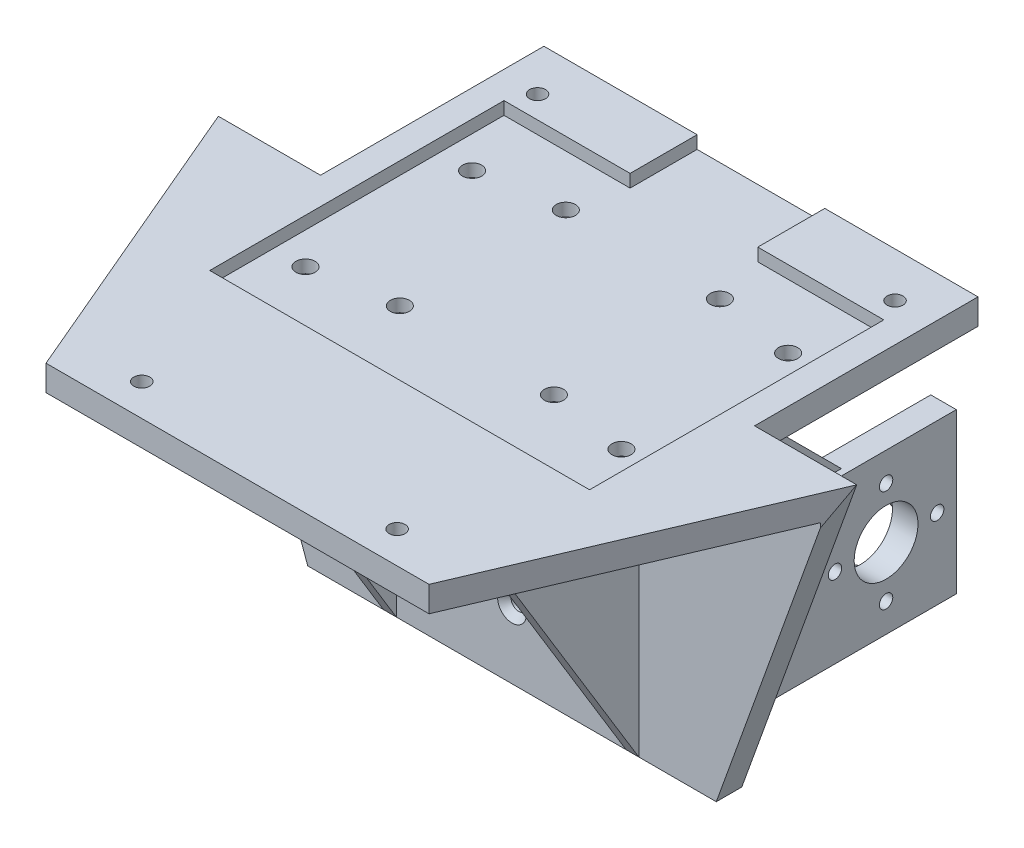
SolidWorks part; units mm, degrees
ref_plane "前视基准面" through (0, 0, 0) normal (0, 0, 1) x (1, 0, 0)
ref_plane "上视基准面" through (0, 0, 0) normal (0, 1, 0) x (1, 0, 0)
ref_plane "右视基准面" through (0, 0, 0) normal (1, 0, 0) x (0, 0, -1)
sketch "草图1" plane through (0, 0, 0) normal (1, 0, 0) x (0, 0, -1)
  line L1 (0, 0) -> (-47, 0)
  line L2 (0, 0) -> (0, 50)
  line L3 (0, 50) -> (-47, 50)
  line L4 (-47, 0) -> (-47, 50)
  point P4 (0, 0)
extrude "凸台-拉伸1" add sketch "草图1" against normal blind 100
sketch "草图2" plane through (0, 0, 0) normal (1, 0, 0) x (0, 0, -1)
  line L1 (-47, 0) -> (-4, 0)
  line L2 (-47, 0) -> (-47, 46)
  line L3 (-47, 46) -> (-4, 46)
  line L4 (-4, 0) -> (-4, 46)
  point P4 (0, 0)
  point P5 (0, 0)
extrude "切除-拉伸1" cut sketch "草图2" against normal through all
sketch "草图6" plane through (0, 0, 4) normal (0, 0, 1) x (1, 0, 0)
  circle A0 centre (-58, 26.5) radius 1
  circle A1 centre (-58, 18.5) radius 1
  circle A2 centre (-58, 10.5) radius 1
  circle A3 centre (-50, 26.5) radius 1
  circle A4 centre (-42, 26.5) radius 1
  circle A5 centre (-50, 18.5) radius 1
  circle A6 centre (-42, 18.5) radius 1
  circle A7 centre (-50, 10.5) radius 1
  circle A8 centre (-42, 10.5) radius 1
hole_wizard "打孔尺寸(%根据十字)槽沉头木螺钉的类型1" positions "草图29" profile "草图30" countersink size "M2" standard "GB" end condition through all
sketch "草图29" plane through (0, 0, 4) normal (0, 0, 1) x (1, 0, 0)
  point P0 (-58, 26.5)
  point P3 (-50, 26.5)
  point P6 (-58, 18.5)
  point P9 (-50, 18.5)
  point P12 (-58, 10.5)
  point P15 (-50, 10.5)
  point P18 (-42, 10.5)
  point P21 (-42, 18.5)
  point P24 (-42, 26.5)
sketch "草图30" plane through (-58, 26.5, 4) normal (1, 0, 0) x (0, -1, 0)
  line L0 (0, 0) -> (0, 4)
  line L1 (0, 4) -> (1.2, 4)
  line L2 (1.2, 4) -> (1.2, 1.05)
  line L3 (1.2, 1.05) -> (2.25, 0)
  line L5 (2.25, 0) -> (0, 0)
  line L6 (-1.2, 1.05) -> (-2.25, 0) construction
  line L11 (0, -6.35) -> (0, 107.95) construction
  dimension "通孔孔直径" = 2.4
  dimension "通孔孔深度" = 4
  dimension "近端锥形沉头孔直径" = 4.5
  dimension "近端锥形沉头孔角度" = 90
sketch "草图31" plane through (0, 0, 0) normal (0, 0, -1) x (-1, 0, 0)
  line L0 (21.4, 6) -> (25.4, 6)
  line L6 (25.4, 6) -> (25.4, 31)
  line L7 (25.4, 31) -> (21.4, 31)
  line L8 (21.4, 6) -> (21.4, 31)
extrude "凸台-拉伸4" add sketch "草图31" along normal blind 37
sketch "草图32" plane through (-25.4, 0, 0) normal (-1, 0, 0) x (0, 0, 1)
  circle A0 centre (-26, 18.5) radius 5
extrude "切除-拉伸2" cut sketch "草图32" against normal up to surface (4 mm away) up to face at (-21.4, 18.5, -18.5)
sketch "草图33" plane through (-25.4, 0, 0) normal (-1, 0, 0) x (0, 0, 1)
  circle A0 centre (-26, 26.5) radius 1.9
  circle A1 centre (-18, 18.5) radius 1.9
  circle A2 centre (-26, 10.5) radius 1.9
  circle A3 centre (-34, 18.5) radius 1.9
extrude "凸台-拉伸5" add sketch "草图33" along normal blind 1.6
sketch "草图34" plane through (-27, 0, 0) normal (-1, 0, 0) x (0, 0, 1)
  circle A0 centre (-26, 26.5) radius 1.05
  circle A1 centre (-18, 18.5) radius 1.05
  circle A2 centre (-26, 10.5) radius 1.05
  circle A3 centre (-34, 18.5) radius 1.05
extrude "切除-拉伸3" cut sketch "草图34" against normal through all
sketch "草图35" plane through (0, 0, 0) normal (0, 0, -1) x (-1, 0, 0)
  line L0 (16, 46) -> (84, 46)
  line L5 (100, 50) -> (0, 50) construction
  line L6 (16, 50) -> (84, 50)
  line L7 (16, 50) -> (16, 46)
  line L9 (84, 50) -> (84, 46)
extrude "凸台-拉伸6" add sketch "草图35" along normal blind 35
sketch "草图36" plane through (0, 50, 0) normal (0, 1, 0) x (1, 0, 0)
  circle A0 centre (-78, 28) radius 1.25
  circle A1 centre (-22, 28) radius 1.25
  circle A2 centre (-70, -42) radius 1.25
  circle A3 centre (-30, -42) radius 1.25
extrude "切除-拉伸4" cut sketch "草图36" against normal up to next
sketch "草图37" plane through (0, 50, 0) normal (0, 1, 0) x (1, 0, 0)
  line L0 (-100, -47) -> (-80, -47)
  line L1 (-100, -47) -> (0, -47) construction
  line L2 (-80, -47) -> (-100, 0)
  line L3 (-100, 0) -> (-100, -47)
  line L4 (0, -47) -> (-20, -47)
  line L5 (-20, -47) -> (0, 0)
  line L6 (0, 0) -> (0, -47)
extrude "切除-拉伸5" cut sketch "草图37" against normal up to next
sketch "草图38" plane through (0, 0, 0) normal (0, 0, -1) x (-1, 0, 0)
  line L0 (0, 0) -> (18, 0)
  line L1 (100, 0) -> (0, 0) construction
  line L2 (18, 0) -> (0, 50)
  line L3 (0, 0) -> (0, 50) construction
  line L4 (0, 50) -> (0, 0)
  line L5 (100, 0) -> (82, 0)
  line L6 (82, 0) -> (100, 50)
  line L7 (100, 50) -> (100, 0)
extrude "切除-拉伸6" cut sketch "草图38" against normal up to next
sketch "草图39" plane through (0, 46, 0) normal (0, -1, 0) x (1, 0, 0)
  circle A0 centre (-70, 42) radius 2.5
  circle A1 centre (-30, 42) radius 2.5
  circle A2 centre (-78, -28) radius 2.5
  circle A3 centre (-22, -28) radius 2.5
extrude "切除-拉伸7" cut sketch "草图39" against normal blind 1.5
sketch "草图40" plane through (0, 50, 0) normal (0, 1, 0) x (1, 0, 0)
  line L0 (-79.75, 24.5) -> (-60, 24.5)
  line L3 (-20.25, 24.5) -> (-20.25, -21.6)
  line L4 (-20.25, -21.6) -> (-79.75, -21.6)
  line L5 (-79.75, -21.6) -> (-79.75, 24.5)
  line L6 (-60, 24.5) -> (-60, 35)
  line L7 (-84, 35) -> (-16, 35) construction
  line L8 (-60, 35) -> (-40, 35)
  line L9 (-40, 35) -> (-40, 24.5)
  line L10 (-40, 24.5) -> (-20.25, 24.5)
extrude "切除-拉伸8" cut sketch "草图40" against normal blind 2
sketch "草图41" plane through (0, 48, 0) normal (0, 1, 0) x (1, 0, 0)
  circle A2 centre (-74.75, 14.5) radius 1.5
  circle A3 centre (-74.75, -11.6) radius 1.5
  circle A4 centre (-25.25, 14.5) radius 1.5
  circle A5 centre (-25.25, -11.6) radius 1.5
extrude "切除-拉伸9" cut sketch "草图41" against normal up to next
sketch "草图42" plane through (0, 48, 0) normal (0, 1, 0) x (1, 0, 0)
  circle A1 centre (-62.07, 16.5) radius 1.5
  circle A2 centre (-37.93, 16.5) radius 1.5
  circle A3 centre (-37.93, -9.5) radius 1.5
  circle A4 centre (-62.07, -9.5) radius 1.5
  point P8 (0, 0)
  point P9 (0, 0)
extrude "切除-拉伸10" cut sketch "草图42" against normal blind 2
ref_plane "基准面2" through (-30.13, 0, 0) normal (1, 0, 0) x (0, 0, -1)
ref_plane "基准面3" through (-70.13, 0, 0) normal (1, 0, 0) x (0, 0, -1)
sketch "草图46" plane through (-30.13, 0, 0) normal (1, 0, 0) x (0, 0, -1)
  line L1 (-47, 46) -> (-4, 46) construction
  line L2 (-32, 46) -> (-4, 0)
rib "筋2" sketch "草图46" sketch "草图46" thickness 2 extrusion direction parallel to sketch draft on no parameters "D1"=2
sketch "草图47" plane through (-70.13, 0, 0) normal (1, 0, 0) x (0, 0, -1)
  line L1 (-32, 46) -> (-4, 0)
rib "筋3" sketch "草图47" sketch "草图47" thickness 2 parameters "D1"=2
sketch "草图48" plane through (0, 0, 0) normal (0, 0, -1) x (-1, 0, 0)
  line L1 (22.4, 31) -> (22.4, 46)
  line L3 (16, 46) -> (84, 46) construction
  line L4 (22.4, 46) -> (24.4, 46)
  line L5 (16, 46) -> (84, 46) construction
  line L6 (24.4, 46) -> (24.4, 31)
  line L7 (24.4, 31) -> (22.4, 31)
extrude "凸台-拉伸7" add sketch "草图48" along normal blind 20
sketch "草图49" plane through (-22.4, 0, 0) normal (1, 0, 0) x (0, 0, -1)
  line L0 (5, 46) -> (20, 46)
  line L1 (20, 46) -> (0, 46) construction
  line L2 (5, 46) -> (20, 31)
  line L3 (20, 46) -> (20, 31)
extrude "切除-拉伸11" cut sketch "草图49" against normal up to next
